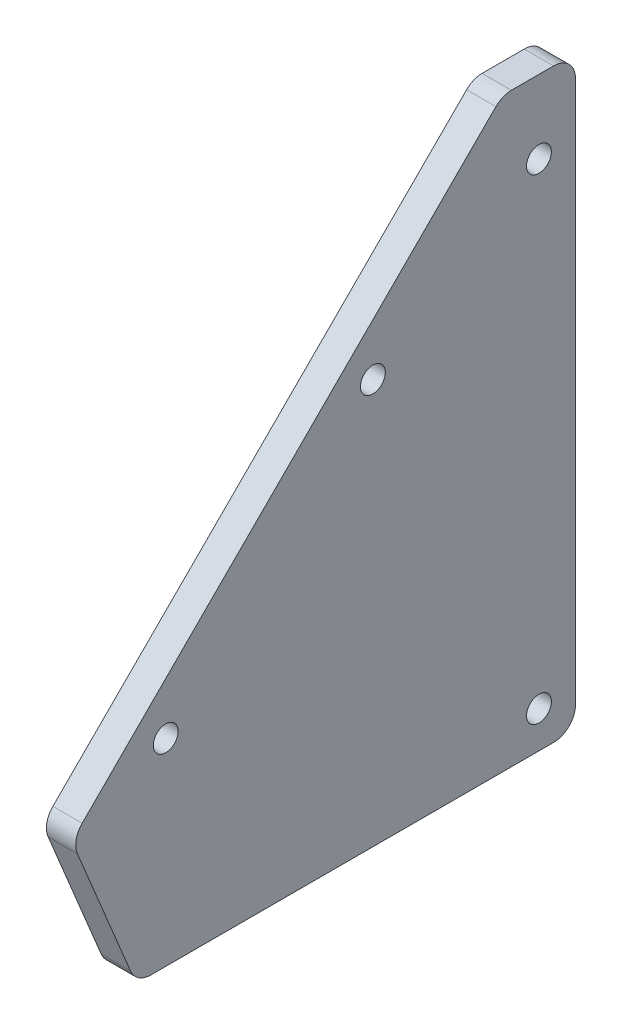
SolidWorks part; units mm, degrees
ref_plane "前视基准面" through (0, 0, 0) normal (0, 0, 1) x (1, 0, 0)
ref_plane "上视基准面" through (0, 0, 0) normal (0, 1, 0) x (1, 0, 0)
ref_plane "右视基准面" through (0, 0, 0) normal (1, 0, 0) x (0, 0, -1)
other "Configuration Table"
sketch "草图3" plane through (0, 0, 0) normal (1, 0, 0) x (0, 0, -1)
  line L0 (0, 0) -> (80, 0)
  line L1 (80, 0) -> (80, 80) construction
  line L2 (80, 80) -> (0, 0)
  line L3 (85, 70) -> (85, 5) construction
  line L4 (34.0381, 26.967) -> (62.3223, 55.2513) construction
  line L5 (62.3223, 55.2513) -> (58.7868, 58.7868) construction
  line L6 (80, 80) -> (90, 80)
  line L7 (90, 80) -> (90, 0)
  line L8 (90, 0) -> (80, 0)
  circle A0 centre (85, 5) radius 1.7
  circle A1 centre (85, 70) radius 1.7
  circle A2 centre (62.3223, 55.2513) radius 1.7
  circle A3 centre (34.0381, 26.967) radius 1.7
  dimension "D3" = 3.4
  dimension "D1" = 45
  dimension "D2" = 5
  dimension "D4" = 5
  dimension "D5" = 80
  dimension "D6" = 65
  dimension "D7" = 5
  dimension "D8" = 40
  dimension "D9" = 30
  dimension "D10" = 10
extrude "凸台-拉伸3" add sketch "草图3" along normal blind 4
chamfer "倒角1" distance 30 1 edges at (2, 0, 0)
fillet "圆角1" radius 3 5 edges at (2, 0, -30) (2, 21.2132, -21.2132) (2, 80, -80) (2, 80, -90) (2, 0, -90)
